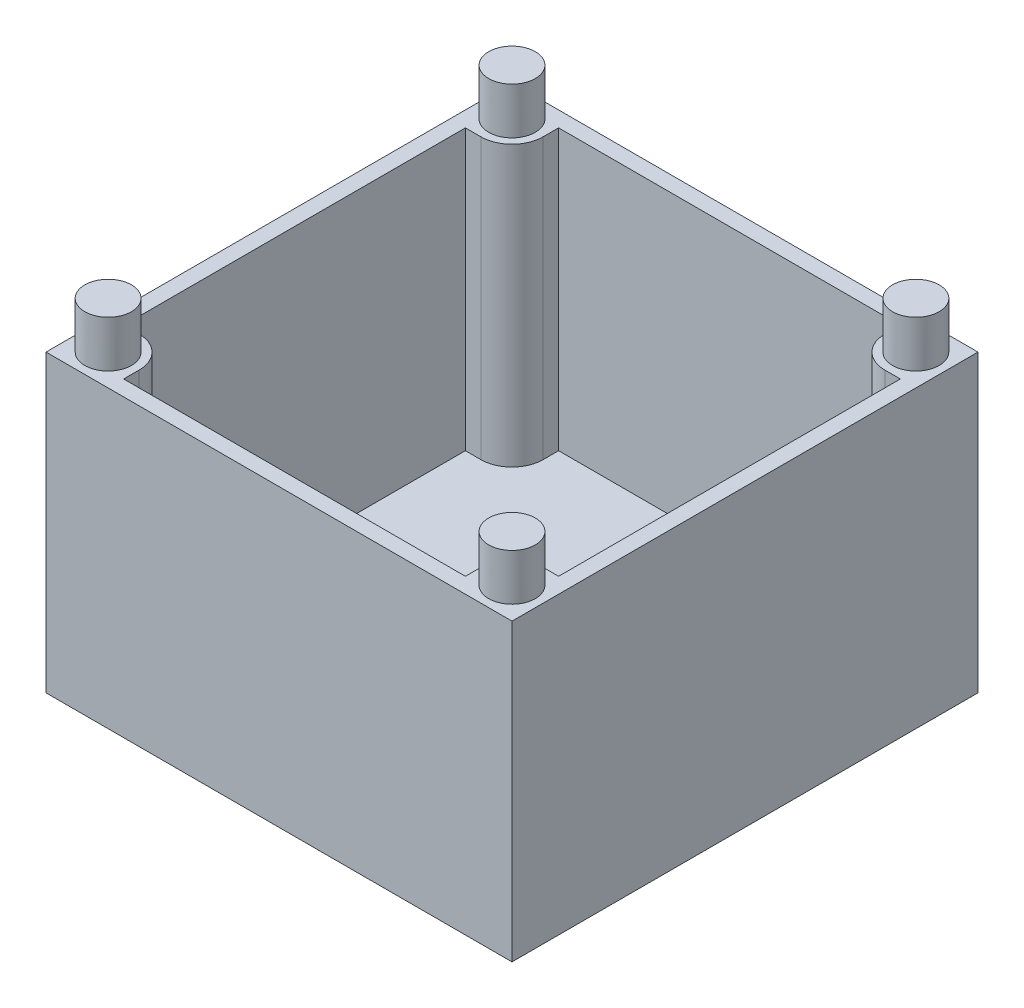
SolidWorks part; units mm, degrees
ref_plane "前视基准面" through (0, 0, 0) normal (0, 0, 1) x (1, 0, 0)
ref_plane "上视基准面" through (0, 0, 0) normal (0, 1, 0) x (1, 0, 0)
ref_plane "右视基准面" through (0, 0, 0) normal (1, 0, 0) x (0, 0, -1)
sketch "草图1" plane through (0, 0, 0) normal (0, 1, 0) x (1, 0, 0)
  line L1 (-7.5, -7.5) -> (7.5, -7.5)
  line L2 (-7.5, -7.5) -> (-7.5, 7.5)
  line L3 (-7.5, 7.5) -> (7.5, 7.5)
  line L4 (7.5, -7.5) -> (7.5, 7.5)
extrude "凸台-拉伸1" add sketch "草图1" along normal blind 9.5
sketch "草图2" plane through (0, 9.5, 0) normal (0, 1, 0) x (-1, 0, 0)
  line L0 (6.5, -5.5) -> (7, -5.5)
  line L1 (5.5, 7) -> (-5.5, 7)
  line L2 (7, 5.5) -> (7, -5.5)
  line L3 (5.5, -7) -> (-5.5, -7)
  line L4 (-7, 5.5) -> (-7, -5.5)
  line L5 (5.5, -6.5) -> (5.5, -7)
  line L6 (-6.5, -5.5) -> (-7, -5.5)
  line L7 (-5.5, -6.5) -> (-5.5, -7)
  line L8 (6.5, 5.5) -> (7, 5.5)
  line L9 (5.5, 6.5) -> (5.5, 7)
  line L10 (-5.5, 6.5) -> (-5.5, 7)
  line L11 (-6.5, 5.5) -> (-7, 5.5)
  arc A0 (6.5, -5.5) -> (5.5, -6.5) centre (6.5, -6.5) ccw
  arc A1 (-6.5, 5.5) -> (-5.5, 6.5) centre (-6.5, 6.5) ccw
  arc A2 (5.5, 6.5) -> (6.5, 5.5) centre (6.5, 6.5) ccw
  arc A3 (-5.5, -6.5) -> (-6.5, -5.5) centre (-6.5, -6.5) ccw
extrude "切除-拉伸1" cut sketch "草图2" against normal blind 9
sketch "草图5" plane through (0, 9.5, 0) normal (0, 1, 0) x (-1, 0, 0)
  circle A0 centre (6.5, -6.5) radius 0.75
  circle A1 centre (6.5, 6.5) radius 0.75
  circle A2 centre (-6.5, 6.5) radius 0.75
  circle A3 centre (-6.5, -6.5) radius 0.75
extrude "凸台-拉伸2" add sketch "草图5" along normal blind 1.5
